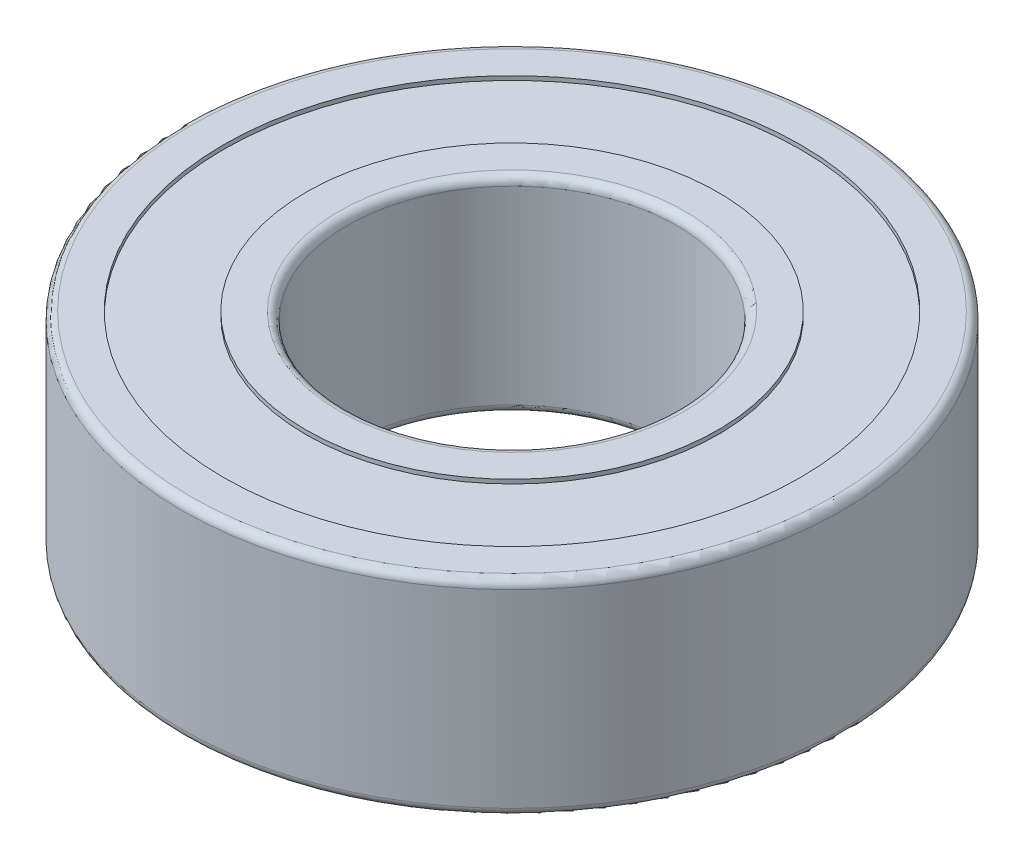
SolidWorks part; units mm, degrees
ref_plane "Front Plane" through (0, 0, 0) normal (0, 0, 1) x (1, 0, 0)
ref_plane "Top Plane" through (0, 0, 0) normal (0, 1, 0) x (1, 0, 0)
ref_plane "Right Plane" through (0, 0, 0) normal (1, 0, 0) x (0, 0, -1)
sketch "Sketch1" plane through (0, 0, 0) normal (0, 1, 0) x (1, 0, 0)
  circle A0 centre (0, 0) radius 4
  circle A1 centre (0, 0) radius 8
  dimension "D1" = 8
  dimension "D2" = 16
extrude "Boss-Extrude1" add sketch "Sketch1" along normal blind 5
fillet "Fillet1" radius 0.2 4 edges at (0, 0, 4) (0, 0, 8) (0, 5, 4) (0, 5, 8)
sketch "Sketch2" plane through (0, 5, 0) normal (0, 1, 0) x (1, 0, 0)
  circle A0 centre (0, 0) radius 5
  circle A1 centre (0, 0) radius 7
  dimension "D1" = 10
  dimension "D2" = 14
extrude "Cut-Extrude1" cut sketch "Sketch2" against normal blind 0.1
sketch "Sketch3" plane through (0, 0, 0) normal (0, -1, 0) x (1, 0, 0)
  circle A0 centre (0, 0) radius 5
  circle A1 centre (0, 0) radius 7
  dimension "D1" = 10
  dimension "D2" = 14
extrude "Cut-Extrude2" cut sketch "Sketch3" against normal blind 0.1
